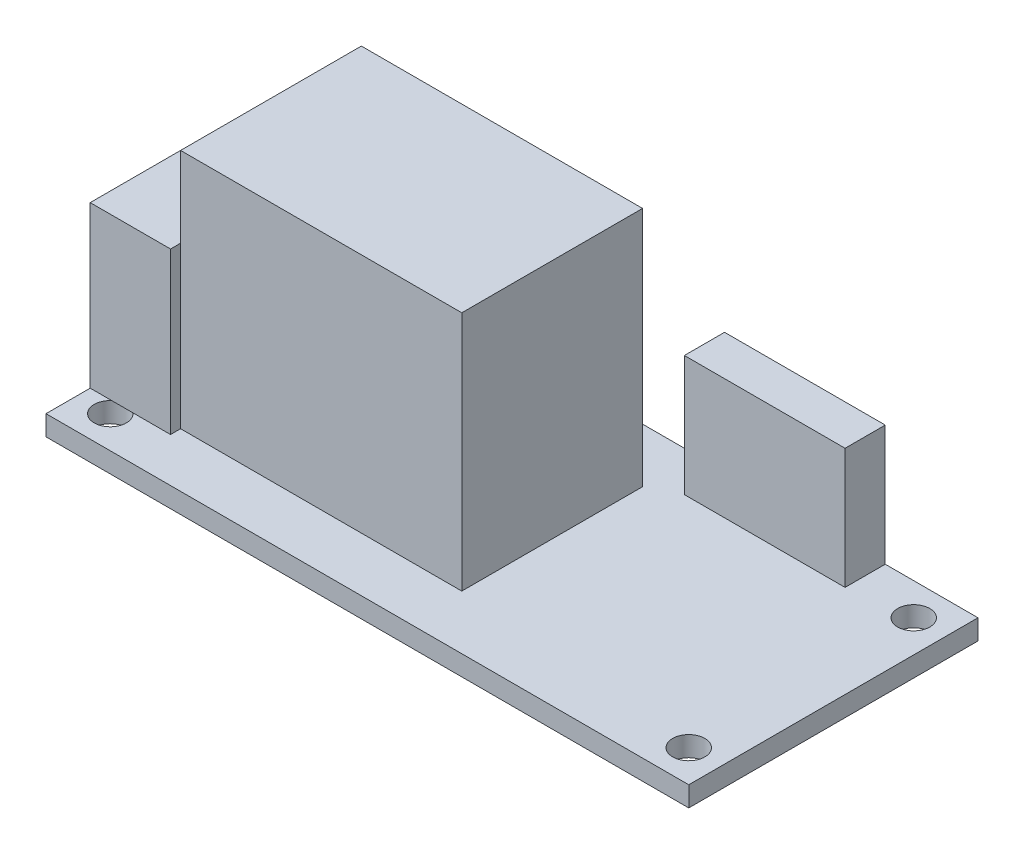
SolidWorks part; units mm, degrees
ref_plane "Front Plane" through (0, 0, 0) normal (0, 0, 1) x (1, 0, 0)
ref_plane "Top Plane" through (0, 0, 0) normal (0, 1, 0) x (1, 0, 0)
ref_plane "Right Plane" through (0, 0, 0) normal (1, 0, 0) x (0, 0, -1)
sketch "Sketch1" plane through (0, 0, 0) normal (0, 1, 0) x (1, 0, 0)
  line L1 (-25.4, 11.43) -> (25.4, 11.43)
  line L2 (-25.4, 11.43) -> (-25.4, -11.43)
  line L3 (-25.4, -11.43) -> (25.4, -11.43)
  line L4 (25.4, 11.43) -> (25.4, -11.43)
  line L5 (-25.4, 11.43) -> (25.4, -11.43) construction
  line L6 (-25.4, -11.43) -> (25.4, 11.43) construction
  point P0 (0, 0)
  dimension "D1" = 50.8
  dimension "D2" = 22.86
extrude "Boss-Extrude1" add sketch "Sketch1" along normal blind 1.5875
sketch "Sketch2" plane through (0, 1.5875, 0) normal (0, 1, 0) x (1, 0, 0)
  line L0 (-25.4, 11.43) -> (-25.4, -11.43) construction
  line L1 (-25.4, -7.9375) -> (-19.05, -7.9375)
  line L2 (-25.4, -7.9375) -> (-25.4, 7.9375)
  line L3 (-25.4, 7.9375) -> (-19.05, 7.9375)
  line L4 (-19.05, -7.9375) -> (-19.05, 7.9375)
  point P11 (-6.8812, 0.6516)
  point P12 (-25.4, 8.2729)
  dimension "D1" = 6.35
  dimension "D2" = 15.875
  dimension "D3" = 7.9375
extrude "Boss-Extrude2" add sketch "Sketch2" along normal blind 12.7
sketch "Sketch3" plane through (0, 1.5875, 0) normal (0, 1, 0) x (1, 0, 0)
  line L1 (-19.05, 7.1437) -> (3.175, 7.1437)
  line L2 (-19.05, 7.1437) -> (-19.05, -7.1438)
  line L3 (-19.05, -7.1438) -> (3.175, -7.1438)
  line L4 (3.175, 7.1437) -> (3.175, -7.1438)
  line L5 (-19.05, 7.1437) -> (3.175, -7.1438) construction
  line L6 (-19.05, -7.1438) -> (3.175, 7.1437) construction
  point P0 (-7.9375, 0)
  point P5 (-19.05, 9.4616)
  point P6 (0, 0)
  dimension "D1" = 22.225
  dimension "D2" = 14.2875
extrude "Boss-Extrude3" add sketch "Sketch3" along normal blind 19.05
sketch "Sketch4" plane through (0, 1.5875, 0) normal (0, 1, 0) x (1, 0, 0)
  line L0 (25.4, 11.43) -> (-25.4, 11.43) construction
  line L1 (5.3694, 11.43) -> (18.0694, 11.43)
  line L2 (5.3694, 11.43) -> (5.3694, 8.255)
  line L3 (5.3694, 8.255) -> (18.0694, 8.255)
  line L4 (18.0694, 11.43) -> (18.0694, 8.255)
  point P6 (5.3694, 11.43)
  dimension "D1" = 3.175
  dimension "D2" = 12.7
extrude "Boss-Extrude4" add sketch "Sketch4" along normal blind 9.525
sketch "Sketch5" plane through (0, 1.5875, 0) normal (0, 1, 0) x (1, 0, 0)
  line L1 (22.86, -8.89) -> (-22.86, -8.89) construction
  line L2 (22.86, -8.89) -> (22.86, 8.89) construction
  line L3 (22.86, 8.89) -> (-22.86, 8.89) construction
  line L4 (-22.86, -8.89) -> (-22.86, 8.89) construction
  line L5 (22.86, -8.89) -> (-22.86, 8.89) construction
  line L6 (22.86, 8.89) -> (-22.86, -8.89) construction
  circle A0 centre (-22.86, 8.89) radius 1.27
  circle A1 centre (22.86, 8.89) radius 1.27
  circle A2 centre (-22.86, -8.89) radius 1.27
  circle A3 centre (22.86, -8.89) radius 1.27
  point P0 (0, 0)
  dimension "D3" = 2.54
  dimension "D1" = 45.72
  dimension "D2" = 17.78
extrude "Cut-Extrude1" cut sketch "Sketch5" against normal through all
